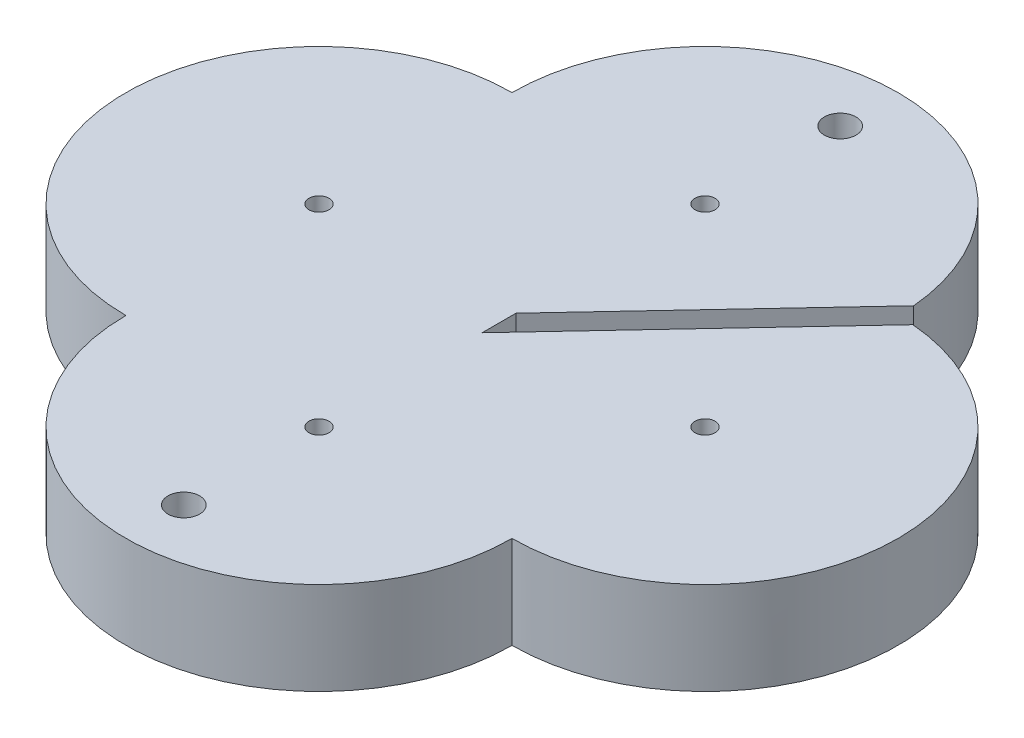
SolidWorks part; units mm, degrees
ref_plane "Ön Düzlem" through (0, 0, 0) normal (0, 0, 1) x (1, 0, 0)
ref_plane "Üst Düzlem" through (0, 0, 0) normal (0, 1, 0) x (1, 0, 0)
ref_plane "Sağ Düzlem" through (0, 0, 0) normal (1, 0, 0) x (0, 0, -1)
sketch "Çizim1" plane through (0, 0, 0) normal (0, 1, 0) x (1, 0, 0)
  line L5 (-65.4545, 25.3409) -> (4.5455, 25.3409)
  line L6 (-65.4545, 25.3409) -> (-65.4545, -44.6591)
  line L7 (-65.4545, -44.6591) -> (4.5455, -44.6591)
  line L8 (4.5455, 25.3409) -> (4.5455, -44.6591)
  arc A8 (19.5455, 40.3409) -> (-80.4545, 40.3409) centre (-30.4545, 40.3409) ccw
  arc A9 (19.5455, -59.6591) -> (19.5455, 40.3409) centre (19.5455, -9.6591) ccw
  arc A10 (-80.4545, -59.6591) -> (19.5455, -59.6591) centre (-30.4545, -59.6591) ccw
  arc A11 (-80.4545, 40.3409) -> (-80.4545, -59.6591) centre (-80.4545, -9.6591) ccw
  circle A12 centre (-115.4545, -9.6591) radius 4
  circle A13 centre (-30.4545, 75.3409) radius 4
  circle A14 centre (54.5455, -9.6591) radius 4
  circle A15 centre (-30.4545, -94.6591) radius 4
  circle A16 centre (-30.4545, 75.3409) radius 9.5
  circle A17 centre (-30.4545, -94.6591) radius 9.5
  dimension "D3" = 8
  dimension "D5" = 35
  dimension "D6" = 35
  dimension "D7" = 35
  dimension "D14" = 19
  dimension "D15" = 19
  dimension "D1" = 100
  dimension "D2" = 100
  dimension "D4" = 35
  dimension "D8" = 15
  dimension "D9" = 15
  dimension "D10" = 15
  dimension "D11" = 15
  dimension "D12" = 70
  dimension "D13" = 70
extrude "Yükseklik-Ekstrüzyon1" add sketch "Çizim1" along normal blind 12 contours A8 A11 A10 A9 A17 A16 A14 A12 L5 L8 L7 L6
sketch "Çizim2" plane through (0, 12, 0) normal (0, 1, 0) x (1, 0, 0)
  arc A13 (19.5455, 40.3409) -> (-80.4545, 40.3409) centre (-30.4545, 40.3409) ccw
  arc A14 (-80.4545, 40.3409) -> (-80.4545, -59.6591) centre (-80.4545, -9.6591) ccw
  arc A15 (-80.4545, -59.6591) -> (19.5455, -59.6591) centre (-30.4545, -59.6591) ccw
  arc A16 (19.5455, -59.6591) -> (19.5455, 40.3409) centre (19.5455, -9.6591) ccw
  arc A17 (19.5455, 40.3409) -> (-80.4545, 40.3409) centre (-30.4545, 40.3409) ccw
  arc A18 (-80.4545, 40.3409) -> (-80.4545, -59.6591) centre (-80.4545, -9.6591) ccw
  arc A19 (-80.4545, -59.6591) -> (19.5455, -59.6591) centre (-30.4545, -59.6591) ccw
  arc A20 (19.5455, -59.6591) -> (19.5455, 40.3409) centre (19.5455, -9.6591) ccw
  dimension "D1" = 0
extrude "Yükseklik-Ekstrüzyon2" add sketch "Çizim2" along normal blind 12
sketch "Çizim3" plane through (0, 24, 0) normal (0, 1, 0) x (1, 0, 0)
  line L0 (-30.4545, 90.3409) -> (-30.4545, -116.372)
  line L1 (19.5455, 40.3409) -> (-30.4545, -13.0156)
  line L2 (19.5455, 40.3409) -> (21.7345, 38.2896)
  line L3 (21.7345, 38.2896) -> (-30.4545, -17.4029)
  line L4 (17.3564, 42.3923) -> (-34.8327, -13.3002)
  line L5 (17.3564, 42.3923) -> (21.7345, 38.2896)
  line L6 (21.7345, 38.2896) -> (31.0304, 48.2095)
  line L7 (31.0304, 48.2095) -> (26.6523, 52.3122)
  line L8 (17.3564, 42.3923) -> (26.6523, 52.3122)
  arc A0 (-30.4545, 90.3409) -> (-80.4545, 40.3409) centre (-30.4545, 40.3409) ccw
  arc A9 (-80.4545, 40.3409) -> (-80.4545, -59.6591) centre (-80.4545, -9.6591) ccw
  arc A10 (-80.4545, -59.6591) -> (19.5455, -59.6591) centre (-30.4545, -59.6591) ccw
  dimension "D2" = 3
extrude "Kes-Ekstrüzyon1" cut sketch "Çizim3" against normal blind 12
sketch "Çizim6" plane through (0, 0, 0) normal (0, -1, 0) x (1, 0, 0)
  circle A0 centre (-115.4545, 9.6591) radius 4
  circle A1 centre (54.5455, 9.6591) radius 4
extrude "Kes-Ekstrüzyon4" cut sketch "Çizim6" against normal blind 20
sketch "Çizim7" plane through (0, 0, 0) normal (0, -1, 0) x (1, 0, 0)
  circle A2 centre (-30.4545, 59.6591) radius 7.2328
  circle A3 centre (-80.4545, 9.6591) radius 7.2328
  circle A4 centre (19.5455, 9.6591) radius 7.2328
  circle A5 centre (-30.4545, -40.3409) radius 7.2328
hole_wizard "M5 Helisarmal için Zıvana matkabı1" positions "3B Çizim1" profile "Çizim8" hole size "M5x0.8" standard "ANSI Metric" end condition up to next
sketch3d "3B Çizim1"
  point P0 (-80.4545, 0, 9.6591)
  point P3 (-30.4545, 0, 59.6591)
  point P6 (19.5455, 0, 9.6591)
  point P9 (-30.4545, 0, -40.3409)
sketch "Çizim8" plane through (-80.4545, 0, 9.6591) normal (1, 0, 0) x (0, 0, -1)
  line L0 (0, 0) -> (0, 24)
  line L1 (0, 24) -> (2.6, 24)
  line L2 (2.6, 24) -> (2.6, 0)
  line L5 (2.6, 0) -> (0, 0)
  line L11 (0, -6.35) -> (0, 107.95) construction
  dimension "Thru Hole Dia." = 5.2
  dimension "Thru Hole Depth" = 24
sketch "Çizim9" plane through (0, 0, 0) normal (0, -1, 0) x (1, 0, 0)
  circle A0 centre (-30.4545, 94.6591) radius 4.1
  circle A1 centre (-30.4545, -75.3409) radius 4.1
  dimension "D1" = 8.2
  dimension "D2" = 8.2
extrude "Kes-Ekstrüzyon5" cut sketch "Çizim9" against normal blind 50
